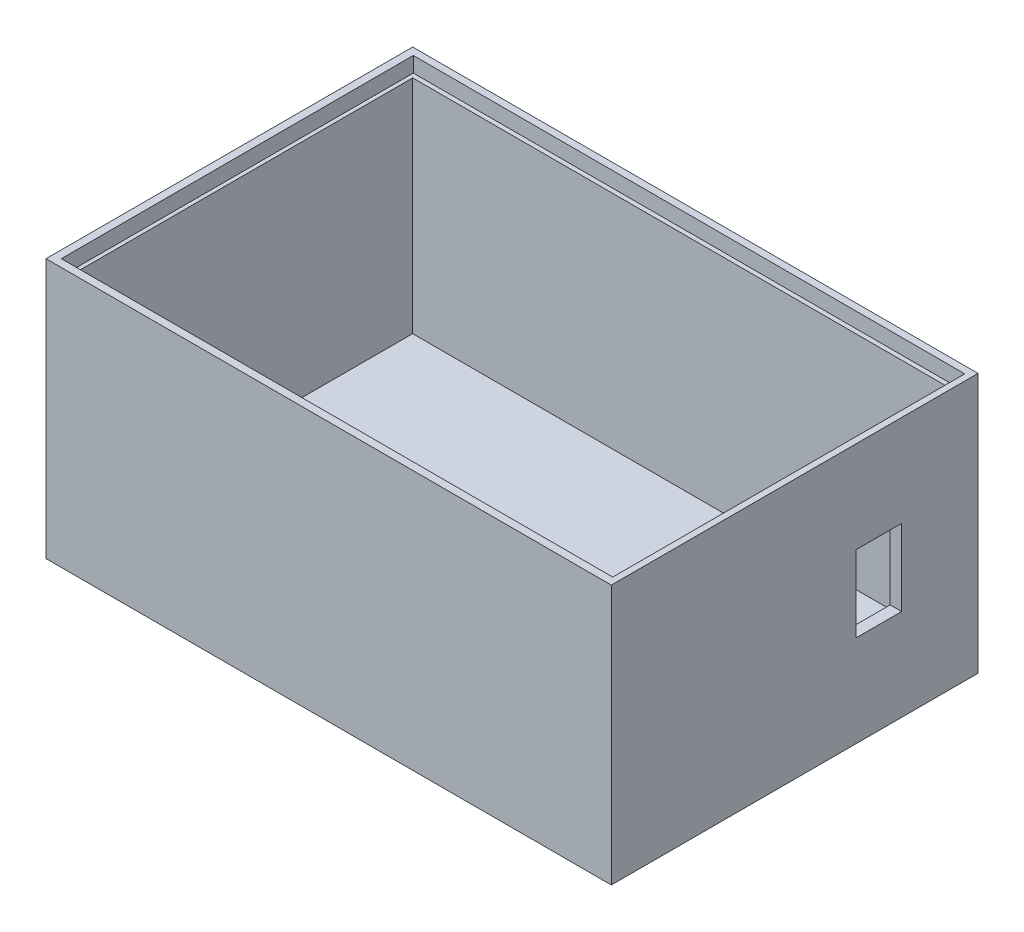
SolidWorks part; units mm, degrees
ref_plane "Front Plane" through (0, 0, 0) normal (0, 0, 1) x (1, 0, 0)
ref_plane "Top Plane" through (0, 0, 0) normal (0, 1, 0) x (1, 0, 0)
ref_plane "Right Plane" through (0, 0, 0) normal (1, 0, 0) x (0, 0, -1)
sketch "Sketch1" plane through (0, 0, 0) normal (0, 1, 0) x (1, 0, 0)
  line L5 (-37, -24) -> (37, -24)
  line L6 (-37, -24) -> (-37, 24)
  line L7 (-37, 24) -> (37, 24)
  line L8 (37, -24) -> (37, 24)
  line L9 (-37, -24) -> (37, 24) construction
  line L10 (-37, 24) -> (37, -24) construction
  point P0 (0, 0)
  dimension "D1" = 74
  dimension "D2" = 48
extrude "Boss-Extrude1" add sketch "Sketch1" along normal blind 34
sketch "Sketch3" plane through (0, 34, 0) normal (0, 1, 0) x (1, 0, 0)
  line L0 (37, 24) -> (-37, 24) construction
  line L1 (-35.5, -22.5) -> (35.5, -22.5)
  line L2 (-35.5, -22.5) -> (-35.5, 22.5)
  line L3 (-35.5, 22.5) -> (35.5, 22.5)
  line L4 (35.5, -22.5) -> (35.5, 22.5)
  line L5 (-35.5, -22.5) -> (35.5, 22.5) construction
  line L6 (-35.5, 22.5) -> (35.5, -22.5) construction
  line L7 (-37, 24) -> (-37, -24) construction
  point P0 (0, 0)
  dimension "D1" = 1.5
  dimension "D2" = 1.5
extrude "Cut-Extrude1" cut sketch "Sketch3" against normal blind 31
sketch "Sketch4" plane through (0, 34, 0) normal (0, 1, 0) x (1, 0, 0)
  line L0 (-37, 24) -> (-37, -24) construction
  line L1 (-36, -23) -> (36.1855, -23)
  line L2 (-36, -23) -> (-36, 23.0801)
  line L3 (-36, 23.0801) -> (36.1855, 23.0801)
  line L4 (36.1855, -23) -> (36.1855, 23.0801)
  line L5 (-37, -24) -> (37, -24) construction
  dimension "D1" = 1
  dimension "D2" = 1
extrude "Cut-Extrude2" cut sketch "Sketch4" against normal blind 2
sketch "Sketch5" plane through (37, 0, 0) normal (1, 0, 0) x (0, 0, -1)
  line L0 (24, 34) -> (24, 0) construction
  line L1 (8, 22) -> (14, 22)
  line L2 (8, 22) -> (8, 12)
  line L3 (8, 12) -> (14, 12)
  line L4 (14, 22) -> (14, 12)
  line L5 (-24, 34) -> (24, 34) construction
  line L6 (-7.9196, 34) -> (-7.9196, 0) construction
  line L7 (-24, 0) -> (24, 0) construction
  point P12 (-7.9196, 17)
  point P13 (8, 17)
  dimension "D1" = 10
  dimension "D2" = 6
  dimension "D3" = 10
extrude "Cut-Extrude3" cut sketch "Sketch5" against normal blind 5
